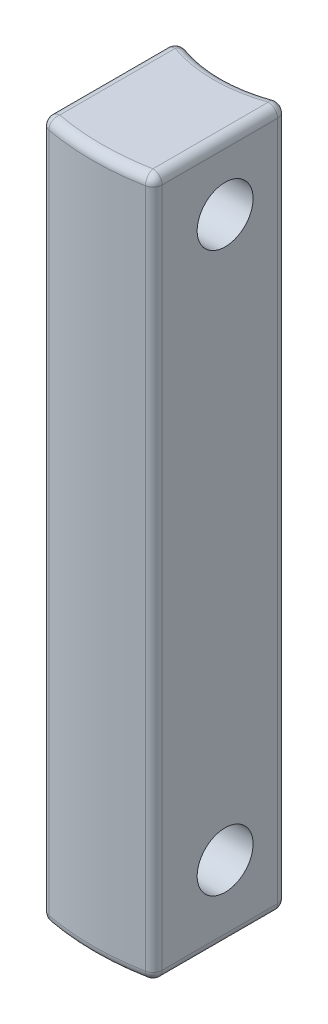
SolidWorks part; units mm, degrees
ref_plane "前视基准面" through (0, 0, 0) normal (0, 0, 1) x (1, 0, 0)
ref_plane "上视基准面" through (0, 0, 0) normal (0, 1, 0) x (1, 0, 0)
ref_plane "右视基准面" through (0, 0, 0) normal (1, 0, 0) x (0, 0, -1)
other "Configuration Table"
sketch "草图1" plane through (0, 0, 0) normal (0, 1, 0) x (1, 0, 0)
  line L0 (0, 0) -> (0, -20.6978) construction
  line L1 (0, -20.6978) -> (-27.356, -20.6978) construction
  line L2 (-6, -13.3475) -> (-6, -28.048)
  line L4 (6, -13.3475) -> (6, -28.048)
  arc A0 (-6, -13.3475) -> (6, -13.3475) centre (0, -0.6984) ccw
  arc A1 (-6, -28.048) -> (6, -28.048) centre (0, -0.6984) ccw
  point P9 (0, 0)
  point P10 (0, 0)
  point P11 (0, 0)
  point P12 (0, -14.6984)
  point P13 (0, -28.6984)
  point P14 (-6, -20.6978)
  dimension "D1" = 14
  dimension "D2" = 28
  dimension "D3" = 12
  dimension "D4" = 14
extrude "凸台-拉伸1" add sketch "草图1" along normal mid plane 75
sketch "草图2" plane through (0, 0, 0) normal (1, 0, 0) x (0, 0, -1)
  line L0 (-20.4755, 0.3678) -> (-20.4755, 33.8451) construction
  circle A0 centre (-20.4755, 30.3678) radius 3
  circle A1 centre (-20.4755, -29.6322) radius 3
  point P6 (0, 0)
  point P7 (0, 0)
  point P8 (-11.8149, 20.7171)
  point P9 (-2.152, 5.093)
  point P10 (0, 0)
  dimension "D1" = 6
  dimension "D2" = 60
  dimension "D3" = 30
extrude "切除-拉伸1" cut sketch "草图2" against normal through all both and the other way through all
fillet "圆角1" radius 1 12 edges at (-6, -37.5, 20.6978) (6, -37.5, 20.6978) (6, 0, 13.3475) (-6, 0, 13.3475) (0, -37.5, 14.6984) (6, 37.5, 20.6978) (-6, 37.5, 20.6978) (0, 37.5, 14.6984) (-6, 0, 28.048) (0, 37.5, 28.6984) (6, 0, 28.048) (0, -37.5, 28.6984)
